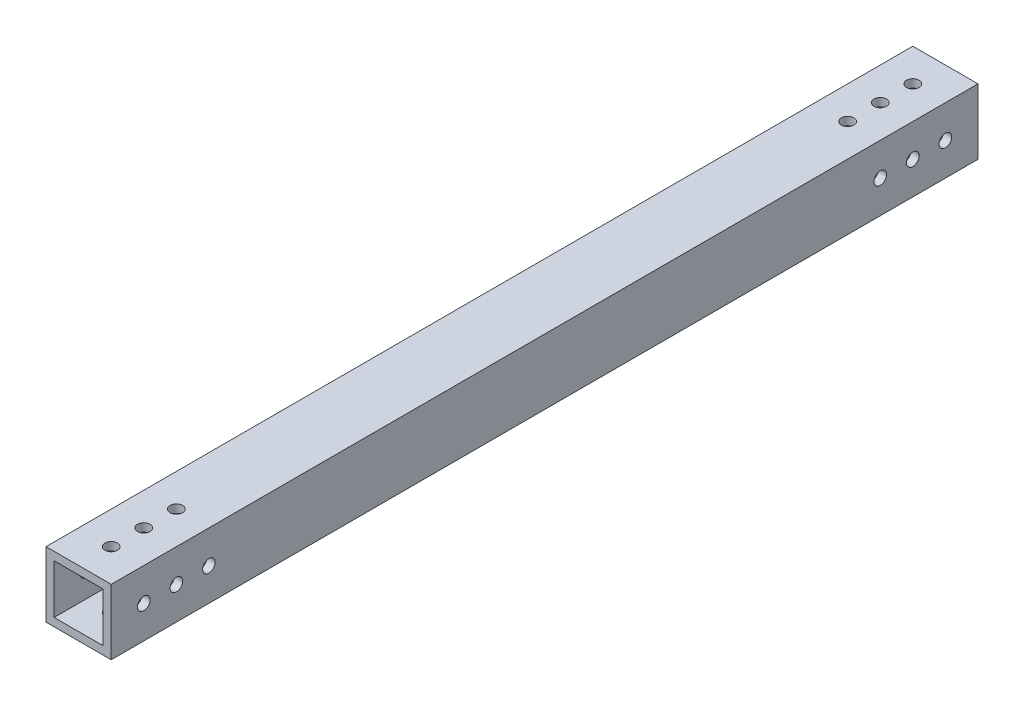
SolidWorks part; units mm, degrees
material "6061 Alloy"
ref_plane "Front Plane" through (0, 0, 0) normal (0, 0, 1) x (1, 0, 0)
ref_plane "Top Plane" through (0, 0, 0) normal (0, 1, 0) x (1, 0, 0)
ref_plane "Right Plane" through (0, 0, 0) normal (1, 0, 0) x (0, 0, -1)
sketch "Sketch1" plane through (0, 0, 0) normal (0, 0, 1) x (1, 0, 0)
  line L1 (0, 0) -> (-25.4, 0)
  line L2 (0, 0) -> (0, 25.4756)
  line L3 (0, 25.4756) -> (-25.4, 25.4756)
  line L4 (-25.4, 0) -> (-25.4, 25.4756)
  dimension "D1" = 25.4
  dimension "D2" = 25.4756
extrude "Extrude-Thin1" add sketch "Sketch1" along normal blind 337.82 thin
hole_wizard "#10 (0.1935) Diameter Hole1" positions "Sketch2" profile "Sketch3" hole size "#10" standard "ANSI Inch" end condition through all
sketch "Sketch2" plane through (0, 0, 0) normal (0, -1, 0) x (-1, 0, 0)
  line L0 (25.4, -337.82) -> (0, -337.82) construction
  line L1 (25.4, -337.82) -> (25.4, 0) construction
  line L2 (25.4, 0) -> (0, 0) construction
  point P0 (12.7, -25.4)
  point P2 (12.7, -12.7)
  point P4 (12.7, -38.1)
  point P6 (12.7, -299.72)
  point P8 (12.7, -312.42)
  point P10 (12.7, -325.12)
  dimension "D1" = 12.7
  dimension "D2" = 12.7
  dimension "D3" = 12.7
  dimension "D4" = 12.7
  dimension "D5" = 12.7
  dimension "D6" = 12.7
  dimension "D7" = 12.7
  dimension "D8" = 12.7
sketch "Sketch3" plane through (-12.7, 0, 25.4) normal (1, 0, 0) x (0, 0, -1)
  line L0 (0, 0) -> (0, 25.4756)
  line L1 (0, 25.4756) -> (2.4574, 25.4756)
  line L2 (2.4574, 25.4756) -> (2.4574, 0)
  line L5 (2.4574, 0) -> (0, 0)
  line L11 (0, -6.35) -> (0, 107.95) construction
  dimension "Thru Hole Dia." = 4.9149
  dimension "Thru Hole Depth" = 25.4756
hole_wizard "#10 (0.1935) Diameter Hole2" positions "Sketch4" profile "Sketch5" hole size "#10" standard "ANSI Inch" end condition through all
sketch "Sketch4" plane through (-25.4, 0, 0) normal (-1, 0, 0) x (0, 0, 1)
  line L0 (0, 3.175) -> (0, 22.3006) construction
  line L1 (337.82, 0) -> (0, 0) construction
  line L3 (337.82, 25.4756) -> (337.82, 0) construction
  line L4 (337.82, 25.4756) -> (0, 25.4756) construction
  point P0 (325.12, 12.6667)
  point P2 (312.42, 12.6667)
  point P4 (299.72, 12.6667)
  point P6 (38.1, 12.7)
  point P8 (25.4, 12.7)
  point P10 (12.7, 12.7)
  dimension "D1" = 12.7
  dimension "D2" = 12.7
  dimension "D3" = 12.7
  dimension "D4" = 12.7
  dimension "D5" = 12.7
  dimension "D6" = 12.7
  dimension "D7" = 12.8089
  dimension "D8" = 12.7
sketch "Sketch5" plane through (-25.4, 12.6667, 325.12) normal (0, 1, 0) x (0, 0, 1)
  line L0 (0, 0) -> (0, 25.4)
  line L1 (0, 25.4) -> (2.4574, 25.4)
  line L2 (2.4574, 25.4) -> (2.4574, 0)
  line L5 (2.4574, 0) -> (0, 0)
  line L11 (0, -6.35) -> (0, 107.95) construction
  dimension "Thru Hole Dia." = 4.9149
  dimension "Thru Hole Depth" = 25.4
